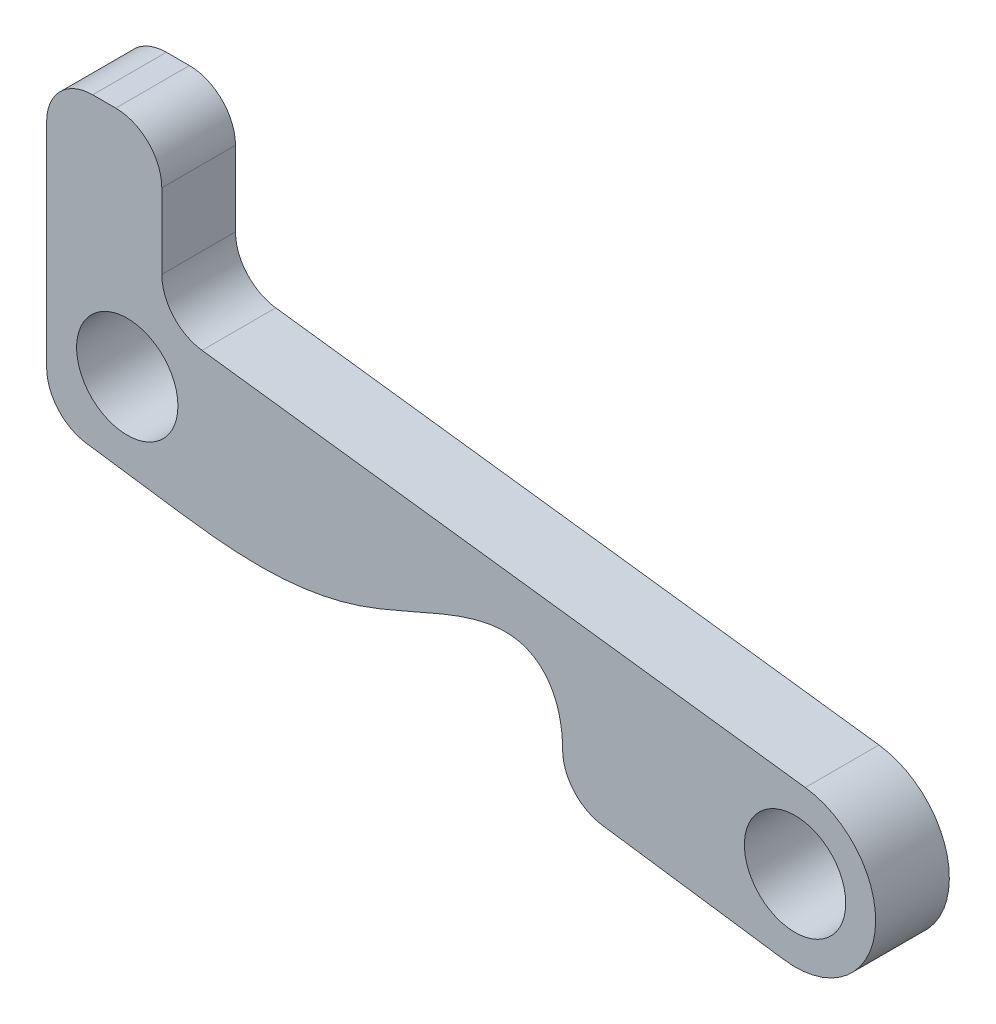
SolidWorks part; units mm, degrees
ref_plane "Front Plane" through (0, 0, 0) normal (0, 0, 1) x (1, 0, 0)
ref_plane "Top Plane" through (0, 0, 0) normal (0, 1, 0) x (1, 0, 0)
ref_plane "Right Plane" through (0, 0, 0) normal (1, 0, 0) x (0, 0, -1)
sketch "Sketch1" plane through (0, 0, 0) normal (0, 0, 1) x (1, 0, 0)
  line L0 (0, 0) -> (1.0886, -0.1577) construction
  line L1 (0.75, 1.4187) -> (14.7215, -0.3641)
  line L2 (-1.75, -1.5741) -> (1.1386, -1.9817)
  line L3 (0, 0) -> (9.4485, 0) construction
  line L4 (0.75, 1.4187) -> (0.75, 4.9259)
  line L5 (0.75, 4.9259) -> (-1.75, 4.9259)
  line L6 (-1.75, 4.9259) -> (-1.75, -1.5741)
  line L7 (12.7129, -3.6151) -> (14.2555, -3.8328)
  line L9 (7.4403, -1.0776) -> (14.5, -2.1) construction
  line L10 (12.7129, -3.6151) -> (10.3128, -3.2764)
  arc A1 (14.2555, -3.8328) -> (14.7215, -0.3641) centre (14.5, -2.1) ccw
  circle A3 centre (14.5, -2.1) radius 1.1
  circle A4 centre (0, 0) radius 1.1
  arc A5 (10.3128, -3.2764) -> (9.4526, -2.2884) centre (10.4526, -2.2862) cw
  spline S0 degree 3 poles (9.4526, -2.2884) (9.4509, -1.4949) (8.489, 0.0589) (4.9309, -2.3008) (2.4877, -2.1721) (1.1386, -1.9817) knots 0.051353 0.051353 0.051353 0.051353 0.215329 0.591995 1 1 1 1
  point P3 (8.25, -1.013)
  dimension "D2" = 1.75
  dimension "D6" = 2.1
  dimension "D9" = 1.75
  dimension "D7" = 2.2
  dimension "D1" = 1
  dimension "D3" = 14.5
  dimension "D4" = 2.5
  dimension "D5" = 6.5
extrude "Boss-Extrude1" add sketch "Sketch1" along normal mid plane 1.6
fillet "Fillet1" radius 1 4 edges at (0.75, 1.4187, 0) (-1.75, -1.5741, 0) (-1.75, 4.9259, 0) (0.75, 4.9259, 0)
